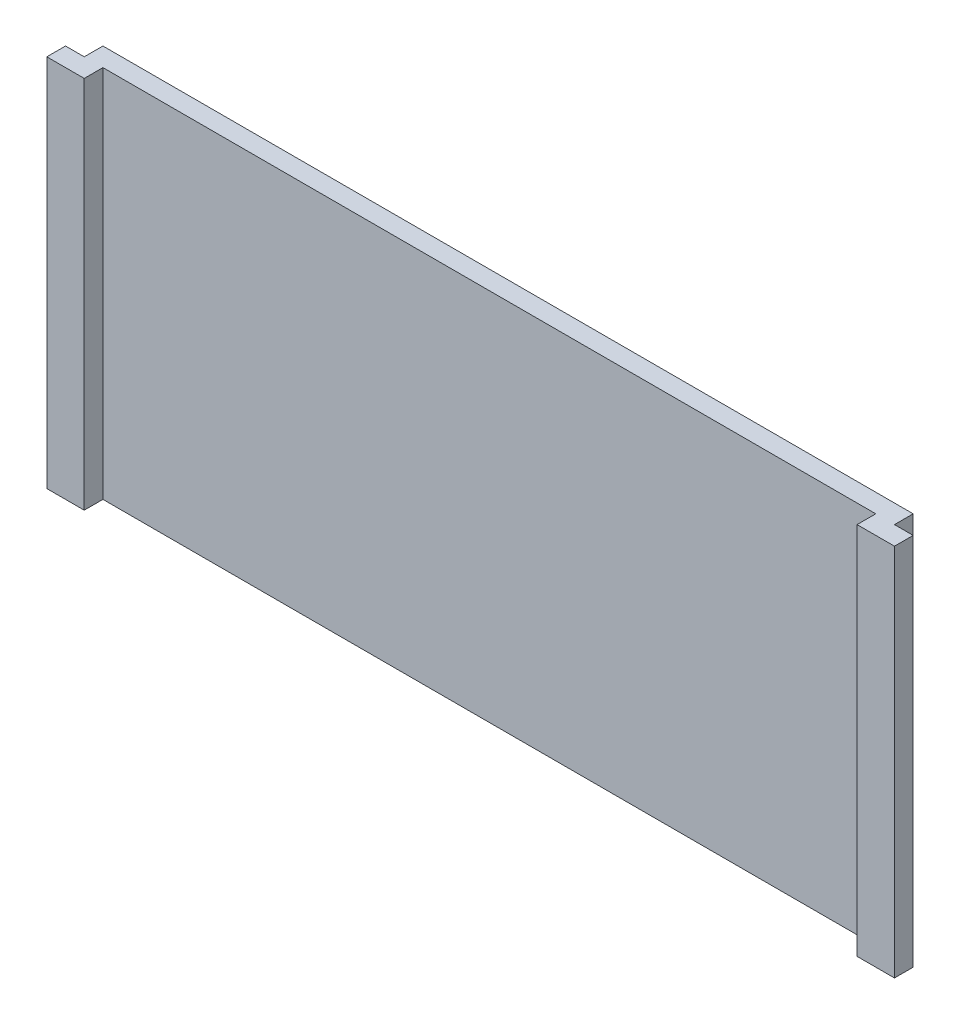
SolidWorks part; units mm, degrees
material "ABS"
ref_plane "前基準面" through (0, 0, 0) normal (0, 0, 1) x (1, 0, 0)
ref_plane "上基準面" through (0, 0, 0) normal (0, 1, 0) x (1, 0, 0)
ref_plane "右基準面" through (0, 0, 0) normal (1, 0, 0) x (0, 0, -1)
sketch "草圖1" plane through (0, 0, 0) normal (0, 0, 1) x (1, 0, 0)
  line L1 (-13.7647, 48.7349) -> (116.2353, 48.7349)
  line L2 (-13.7647, 48.7349) -> (-13.7647, -11.2651)
  line L3 (-13.7647, -11.2651) -> (116.2353, -11.2651)
  line L4 (116.2353, 48.7349) -> (116.2353, -11.2651)
  dimension "D1" = 130
  dimension "D2" = 60
extrude "填料-伸長1" add sketch "草圖1" along normal blind 3
sketch "草圖2" plane through (0, 0, 3) normal (0, 0, 1) x (1, 0, 0)
  line L0 (-13.7647, -11.2651) -> (116.2353, -11.2651) construction
  line L1 (-13.7647, 48.7349) -> (-10.7647, 48.7349)
  line L2 (-13.7647, 48.7349) -> (-13.7647, -11.2651)
  line L3 (-13.7647, -11.2651) -> (-10.7647, -11.2651)
  line L4 (-10.7647, 48.7349) -> (-10.7647, -11.2651)
  line L5 (-13.7647, -11.2651) -> (-13.7647, 48.7349)
  line L6 (116.2353, 48.7349) -> (113.2353, 48.7349)
  line L7 (116.2353, 48.7349) -> (116.2353, -11.2651)
  line L8 (116.2353, -11.2651) -> (113.2353, -11.2651)
  line L9 (113.2353, 48.7349) -> (113.2353, -11.2651)
  line L10 (-13.7647, -11.2651) -> (-16.7647, -11.2651)
  line L11 (-13.7647, 48.7349) -> (-16.7647, 48.7349)
  line L12 (-16.7647, -11.2651) -> (-16.7647, 48.7349)
  line L13 (116.2353, 48.7349) -> (116.2353, -11.2651)
  line L14 (116.2353, 48.7349) -> (119.2353, 48.7349)
  line L15 (116.2353, -11.2651) -> (119.2353, -11.2651)
  line L16 (119.2353, 48.7349) -> (119.2353, -11.2651)
  line M5 (-13.7647, 48.7349) -> (-13.7647, -11.2651)
  line M6 (-13.7647, -11.2651) -> (116.2353, -11.2651)
  line M7 (116.2353, -11.2651) -> (116.2353, 48.7349)
  line M8 (116.2353, 48.7349) -> (-13.7647, 48.7349)
  dimension "D1" = 3
  dimension "D2" = 3
  dimension "D3" = 3
  dimension "D4" = 3
extrude "填料-伸長2" add sketch "草圖2" along normal blind 3 contours L12 L10 L11 M5 | L4 M8 M5 M6 | L16 L14 L15 M7 | L9 M8 M6 M7
